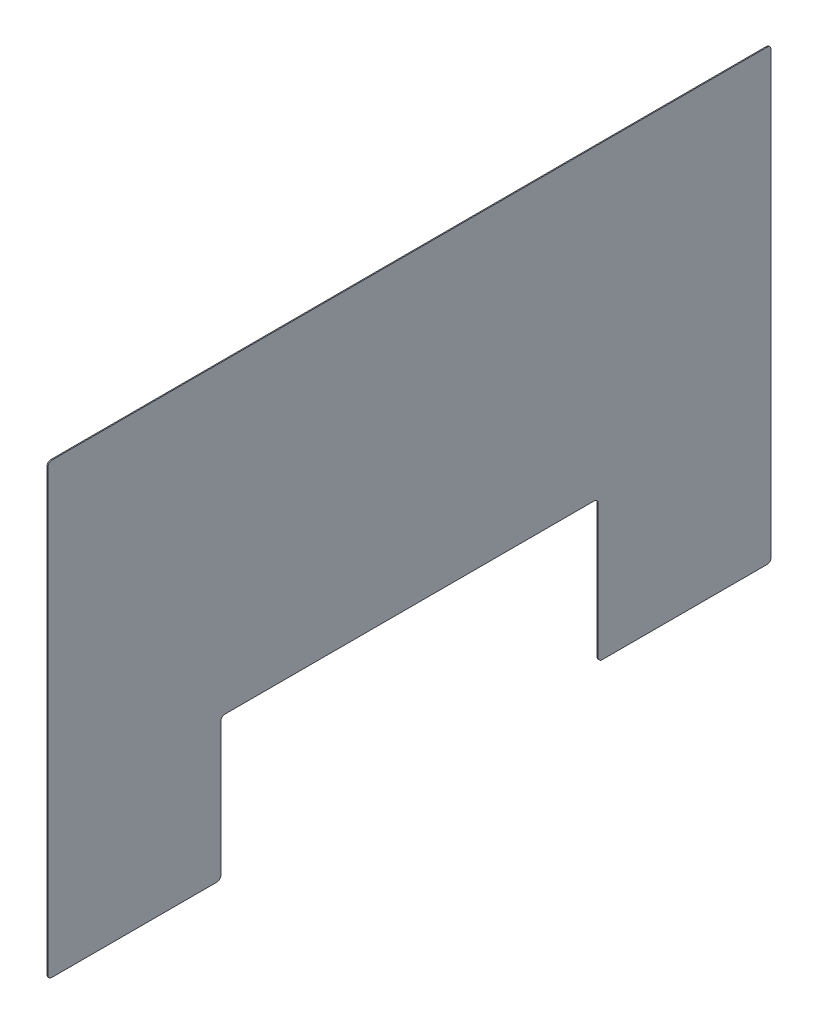
SolidWorks part; units mm, degrees
material "PC High Viscosity"
ref_plane "Front Plane" through (0, 0, 0) normal (0, 0, 1) x (1, 0, 0)
ref_plane "Top Plane" through (0, 0, 0) normal (0, 1, 0) x (1, 0, 0)
ref_plane "Right Plane" through (0, 0, 0) normal (1, 0, 0) x (0, 0, -1)
sketch "Sketch1" plane through (0, 0, 0) normal (1, 0, 0) x (0, 0, -1)
  line L0 (-304.8, -361.95) -> (-584.2, -361.95)
  line L1 (584.2, -361.95) -> (304.8, -361.95)
  line L2 (584.2, -361.95) -> (584.2, 361.95)
  line L3 (584.2, 361.95) -> (-584.2, 361.95)
  line L4 (-584.2, -361.95) -> (-584.2, 361.95)
  line L5 (584.2, -361.95) -> (-584.2, 361.95) construction
  line L6 (584.2, 361.95) -> (-584.2, -361.95) construction
  line L7 (304.8, -133.35) -> (-304.8, -133.35)
  line L8 (304.8, -133.35) -> (304.8, -361.95)
  line L10 (-304.8, -133.35) -> (-304.8, -361.95)
  line L11 (304.8, -133.35) -> (-304.8, -361.95) construction
  line L12 (304.8, -361.95) -> (-304.8, -133.35) construction
  point P0 (0, 0)
  point P6 (0, -247.65)
  dimension "D1" = 723.9
  dimension "D2" = 1168.4
  dimension "D3" = 279.4
  dimension "D4" = 279.4
  dimension "D5" = 228.6
extrude "Boss-Extrude1" add sketch "Sketch1" along normal blind 1.5875
fillet "Fillet1" radius 6.35 8 edges at (0.7937, 361.95, -584.2) (0.7937, -361.95, -584.2) (0.7937, -361.95, -304.8) (0.7937, -133.35, -304.8) (0.7937, -133.35, 304.8) (0.7937, -361.95, 304.8) (0.7937, -361.95, 584.2) (0.7937, 361.95, 584.2)
